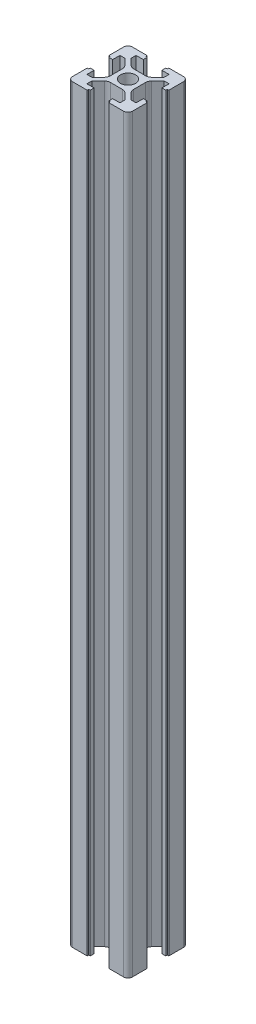
SolidWorks part; units mm, degrees
material "1060 Alloy"
ref_plane "Front Plane" through (0, 0, 0) normal (0, 0, 1) x (1, 0, 0)
ref_plane "Top Plane" through (0, 0, 0) normal (0, 1, 0) x (1, 0, 0)
ref_plane "Right Plane" through (0, 0, 0) normal (1, 0, 0) x (0, 0, -1)
sketch "Sketch1" plane through (0, 0, 0) normal (0, 1, 0) x (1, 0, 0)
  line L1 (8.5, 10) -> (-8.5, 10)
  line L2 (10, 8.5) -> (10, -8.5)
  line L3 (8.5, -10) -> (-8.5, -10)
  line L4 (-10, 8.5) -> (-10, -8.5)
  line L5 (10, 10) -> (-10, -10) construction
  line L6 (10, -10) -> (-10, 10) construction
  arc A0 (-8.5, -10) -> (-10, -8.5) centre (-8.5, -8.5) cw
  arc A1 (10, -8.5) -> (8.5, -10) centre (8.5, -8.5) cw
  arc A2 (8.5, 10) -> (10, 8.5) centre (8.5, 8.5) cw
  arc A3 (-8.5, 10) -> (-10, 8.5) centre (-8.5, 8.5) ccw
  point P0 (0, 0)
  dimension "D3" = 1.5
  dimension "D1" = 20
  dimension "D2" = 20
extrude "Boss-Extrude1" add sketch "Sketch1" along normal blind 250
sketch "Sketch4" plane through (0, 0, 0) normal (0, 1, 0) x (1, 0, 0)
  circle A0 centre (0, 0) radius 2.5
  dimension "D1" = 5
extrude "Cut-Extrude2" cut sketch "Sketch4" along normal through all
sketch "Sketch2" plane through (0, 0, 0) normal (0, -1, 0) x (1, 0, 0)
  line L0 (-3.6, -10) -> (-3.6, -9.5)
  line L1 (8.5, -10) -> (-8.5, -10) construction
  line L2 (-3.6, -9.5) -> (-3.1, -9.5)
  line L3 (-3.1, -9.5) -> (-3.1, -8.2)
  line L4 (-3.1, -8.2) -> (-5.5, -8.2)
  line L5 (-5.5, -8.2) -> (-5.5, -6.5607)
  line L6 (-5.5, -6.5607) -> (-2.8393, -3.9)
  line L7 (-2.8393, -3.9) -> (2.8393, -3.9)
  line L8 (2.8393, -3.9) -> (5.5, -6.5607)
  line L9 (5.5, -6.5607) -> (5.5, -8.2)
  line L10 (5.5, -8.2) -> (3.1, -8.2)
  line L11 (3.1, -8.2) -> (3.1, -9.5)
  line L12 (3.1, -9.5) -> (3.6, -9.5)
  line L13 (3.6, -9.5) -> (3.6, -10)
  line L14 (-5.5, -6.5607) -> (5.5, -6.5607) construction
  line L15 (-3.1, -8.2) -> (3.1, -8.2) construction
  line L16 (3.1, -9.5) -> (-3.1, -9.5) construction
  line L17 (-3.6, -10) -> (3.6, -10)
  line L18 (-9.5607, -9.5607) -> (9.5607, 9.5607) construction
  line L19 (9.5607, -9.5607) -> (-9.5607, 9.5607) construction
  arc A0 (-10, -8.5) -> (-8.5, -10) centre (-8.5, -8.5) ccw construction
  arc A1 (10, 8.5) -> (8.5, 10) centre (8.5, 8.5) ccw construction
  arc A2 (8.5, -10) -> (10, -8.5) centre (8.5, -8.5) ccw construction
  arc A3 (-8.5, 10) -> (-10, 8.5) centre (-8.5, 8.5) ccw construction
  point P5 (0, -3.9)
  point P17 (0, -9.5)
  point P18 (0, -8.2)
  point P20 (0, -6.5607)
  point P21 (0, -10)
  dimension "D1" = 7.2
  dimension "D2" = 6.2
  dimension "D3" = 0.5
  dimension "D4" = 11
  dimension "D5" = 6.1
  dimension "D6" = 1.8
  dimension "D7" = 0.75
extrude "Cut-Extrude1" cut sketch "Sketch2" against normal through all
fillet "Fillet1" radius 2 2 edges at (2.8393, 125, -3.9) (-2.8393, 125, -3.9)
pattern_circular "CirPattern1" count 4 over 360 about axis through (0, 0, 0) along (0, 1, 0) of "Cut-Extrude1", "Fillet1"
